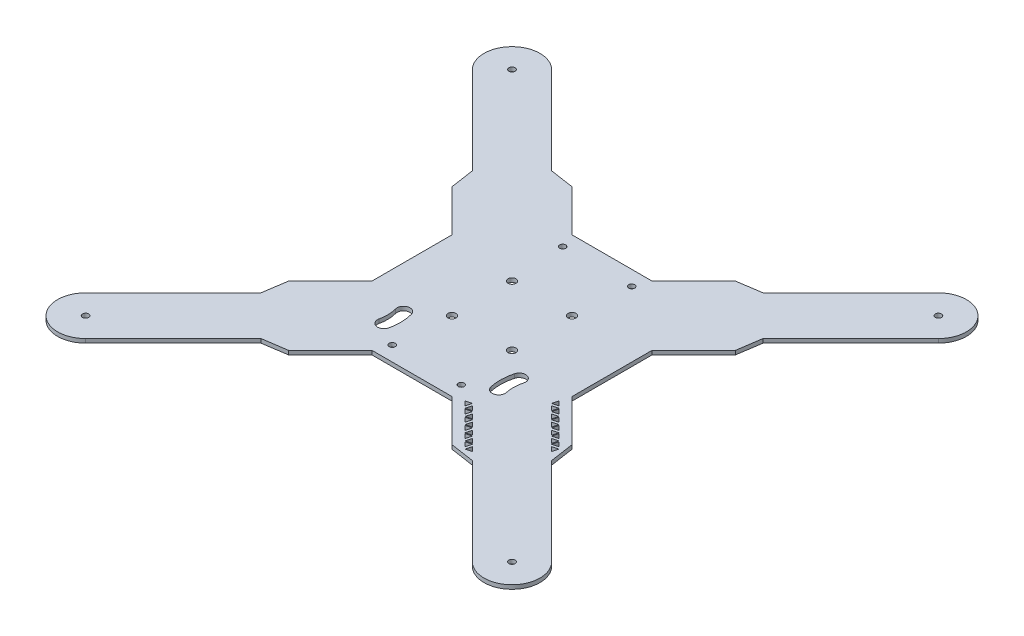
SolidWorks part; units mm, degrees
ref_plane "Front Plane" through (0, 0, 0) normal (0, 0, 1) x (1, 0, 0)
ref_plane "Top Plane" through (0, 0, 0) normal (0, 1, 0) x (1, 0, 0)
ref_plane "Right Plane" through (0, 0, 0) normal (1, 0, 0) x (0, 0, -1)
sketch "Sketch1" plane through (0, 0, 0) normal (0, 1, 0) x (1, 0, 0)
  line L0 (50, 50) -> (106.5685, 106.5685) construction
  line L1 (-50, 50) -> (50, 50)
  line L2 (-50, 50) -> (-50, -50)
  line L3 (-50, -50) -> (50, -50)
  line L4 (50, 50) -> (50, -50)
  line L5 (-50, 50) -> (50, -50) construction
  line L6 (-50, -50) -> (50, 50) construction
  line L7 (0, 97.9754) -> (0, -94.9622) construction
  line L8 (72.6274, 52.8284) -> (70.8284, 40.8284)
  line L9 (70.8284, 40.8284) -> (50, 20)
  line L10 (-86.7005, 0) -> (97.3001, 0) construction
  line L11 (-116.468, 96.669) -> (-72.6274, 52.8284)
  line L12 (-50, 50) -> (-106.5685, 106.5685) construction
  line L13 (-40.8284, 70.8284) -> (-20, 50)
  line L14 (40.8284, 70.8284) -> (20, 50)
  line L15 (-50, -50) -> (-106.5685, -106.5685) construction
  line L16 (50, -50) -> (106.5685, -106.5685) construction
  line L17 (52.8284, 72.6274) -> (40.8284, 70.8284)
  line L18 (96.669, 116.468) -> (52.8284, 72.6274)
  line L19 (116.468, 96.669) -> (72.6274, 52.8284)
  line L20 (-50, -50) -> (50, -50)
  line L21 (50, -50) -> (106.5685, -106.5685) construction
  line L22 (116.468, -96.669) -> (72.6274, -52.8284)
  line L23 (96.669, -116.468) -> (52.8284, -72.6274)
  line L24 (52.8284, -72.6274) -> (40.8284, -70.8284)
  line L25 (-72.6274, 52.8284) -> (-70.8284, 40.8284)
  line L26 (-70.8284, 40.8284) -> (-50, 20)
  line L27 (-52.8284, 72.6274) -> (-40.8284, 70.8284)
  line L28 (-96.669, 116.468) -> (-52.8284, 72.6274)
  line L29 (40.8284, -70.8284) -> (20, -50)
  line L30 (70.8284, -40.8284) -> (50, -20)
  line L31 (72.6274, -52.8284) -> (70.8284, -40.8284)
  line L32 (-50, -50) -> (-106.5685, -106.5685) construction
  line L33 (-96.669, -116.468) -> (-52.8284, -72.6274)
  line L34 (-52.8284, -72.6274) -> (-40.8284, -70.8284)
  line L35 (-70.8284, -40.8284) -> (-50, -20)
  line L36 (-72.6274, -52.8284) -> (-70.8284, -40.8284)
  line L37 (-40.8284, -70.8284) -> (-20, -50)
  line L38 (-116.468, -96.669) -> (-72.6274, -52.8284)
  circle A0 centre (106.5685, 106.5685) radius 14
  circle A1 centre (-106.5685, 106.5685) radius 14
  circle A2 centre (-106.5685, -106.5685) radius 14
  circle A3 centre (106.5685, -106.5685) radius 14
  circle A4 centre (-106.5685, -106.5685) radius 1.556
  circle A5 centre (106.5685, -106.5685) radius 1.556
  circle A6 centre (106.5685, 106.5685) radius 1.556
  circle A7 centre (-106.5685, 106.5685) radius 1.556
  circle A8 centre (106.5685, -106.5685) radius 1.556
  circle A9 centre (-106.5685, -106.5685) radius 1.556
  point P0 (0, 0)
  dimension "D3" = 28
  dimension "D4" = 3.112
  dimension "D1" = 100
  dimension "D2" = 100
  dimension "D5" = 80
  dimension "D6" = 12
  dimension "D7" = 30
  dimension "D8" = 62
  dimension "D9" = 29.4558
extrude "Boss-Extrude1" add sketch "Sketch1" along normal blind 2
sketch "Sketch2" plane through (0, 0, 0) normal (1, 0, 0) x (0, 0, -1)
  line L0 (0, 0) -> (0, 60) construction
  dimension "D1" = 60
sketch "Sketch3" plane through (0, 2, 0) normal (0, 1, 0) x (1, 0, 0)
  line L0 (0, 50) -> (0, -50) construction
  line L1 (-20, 50) -> (20, 50) construction
  line L2 (-20, -50) -> (20, -50) construction
  line L3 (-17.25, 50) -> (-17.25, -50) construction
  line L4 (17.25, 50) -> (17.25, -50) construction
  line L5 (-17.25, 0) -> (17.25, 0) construction
  circle A8 centre (-15, 15) radius 2
  circle A9 centre (-17.25, 42.6) radius 1.5
  circle A10 centre (15, 15) radius 2
  circle A11 centre (17.25, 42.6) radius 1.5
  circle A12 centre (15, -15) radius 2
  circle A13 centre (-15, -15) radius 2
  circle A14 centre (17.25, -42.6) radius 1.5
  circle A15 centre (-17.25, -42.6) radius 1.5
  dimension "D2" = 4
  dimension "D3" = 15
  dimension "D4" = 27.6
  dimension "D5" = 3
  dimension "D6" = 15
  dimension "D7" = 17.25
  dimension "D1" = 17.25
extrude "Cut-Extrude1" cut sketch "Sketch3" against normal blind 10
sketch "Sketch4" plane through (0, 2, 0) normal (0, 1, 0) x (1, 0, 0)
  line L0 (0, -24.6733) -> (0, 24.6733) construction
  arc A0 (28.8923, -25.3253) -> (28.6598, -35.3226) centre (49.6054, -30.8083) ccw construction
  arc A5 (25.7505, -24.4936) -> (25.4828, -36.0073) centre (49.6054, -30.8083) ccw
  arc A6 (32.0341, -26.1569) -> (31.8369, -34.6378) centre (49.6054, -30.8083) ccw
  arc A7 (32.0341, -26.1569) -> (25.7505, -24.4936) centre (28.8923, -25.3253) ccw
  arc A8 (25.4828, -36.0073) -> (31.8369, -34.6378) centre (28.6598, -35.3226) ccw
  arc A9 (-28.8923, -25.3253) -> (-28.6598, -35.3226) centre (-49.6054, -30.8083) cw construction
  arc A10 (-25.7505, -24.4936) -> (-25.4828, -36.0073) centre (-49.6054, -30.8083) cw
  arc A11 (-32.0341, -26.1569) -> (-31.8369, -34.6378) centre (-49.6054, -30.8083) cw
  arc A12 (-32.0341, -26.1569) -> (-25.7505, -24.4936) centre (-28.8923, -25.3253) cw
  arc A13 (-25.4828, -36.0073) -> (-31.8369, -34.6378) centre (-28.6598, -35.3226) cw
  point P3 (28.1847, -30.3102)
  point P8 (48.4255, -30.805)
  point P9 (28.5792, -22.729)
  point P10 (25.9159, -28.1417)
  point P11 (49.9586, -24.5797)
  point P17 (-28.1847, -30.3102)
  dimension "D1" = 10
  dimension "D2" = 6.5
extrude "Cut-Extrude2" cut sketch "Sketch4" against normal through all both
sketch "Sketch5" plane through (0, 2, 0) normal (0, 1, 0) x (1, 0, 0)
  line L0 (25.1819, -48.6551) -> (27.3032, -50.7765)
  line L3 (25.1819, -48.6551) -> (28.0797, -47.8787)
  line L4 (28.0797, -47.8787) -> (27.3032, -50.7765)
  line L12 (116.468, -116.468) -> (36.1807, -36.1807) construction
  line L25 (40.8284, -70.8284) -> (20, -50) construction
  line L26 (52.8284, -72.6274) -> (28.0797, -47.8787) construction
  line L30 (27.3032, -50.7765) -> (48.5062, -71.9795) construction
  line L31 (52.8284, -72.6274) -> (40.8284, -70.8284) construction
  line L32 (29.0797, -48.8787) -> (28.3032, -51.7765)
  line L33 (28.3032, -51.7765) -> (31.201, -51)
  line L34 (31.201, -51) -> (29.0797, -48.8787)
  line L35 (28.7174, -52.1907) -> (30.8388, -54.312)
  line L36 (28.7174, -52.1907) -> (31.6152, -51.4142)
  line L37 (31.6152, -51.4142) -> (30.8388, -54.312)
  line L38 (32.6152, -52.4142) -> (31.8388, -55.312)
  line L39 (31.8388, -55.312) -> (34.7365, -54.5355)
  line L40 (34.7365, -54.5355) -> (32.6152, -52.4142)
  line L41 (32.253, -55.7262) -> (34.3743, -57.8475)
  line L42 (32.253, -55.7262) -> (35.1508, -54.9497)
  line L43 (35.1508, -54.9497) -> (34.3743, -57.8475)
  line L44 (36.1508, -55.9497) -> (35.3743, -58.8475)
  line L45 (35.3743, -58.8475) -> (38.2721, -58.0711)
  line L46 (38.2721, -58.0711) -> (36.1508, -55.9497)
  line L47 (35.7885, -59.2617) -> (37.9098, -61.3831)
  line L48 (35.7885, -59.2617) -> (38.6863, -58.4853)
  line L49 (38.6863, -58.4853) -> (37.9098, -61.3831)
  line L50 (39.6863, -59.4853) -> (38.9098, -62.3831)
  line L51 (38.9098, -62.3831) -> (41.8076, -61.6066)
  line L52 (41.8076, -61.6066) -> (39.6863, -59.4853)
  line L53 (39.324, -62.7973) -> (41.4454, -64.9186)
  line L54 (39.324, -62.7973) -> (42.2218, -62.0208)
  line L55 (42.2218, -62.0208) -> (41.4454, -64.9186)
  line L56 (43.2218, -63.0208) -> (42.4454, -65.9186)
  line L57 (42.4454, -65.9186) -> (45.3431, -65.1421)
  line L58 (45.3431, -65.1421) -> (43.2218, -63.0208)
  line L59 (42.8596, -66.3328) -> (44.9809, -68.4541)
  line L60 (42.8596, -66.3328) -> (45.7574, -65.5563)
  line L61 (45.7574, -65.5563) -> (44.9809, -68.4541)
  line L62 (46.7574, -66.5563) -> (45.9809, -69.4541)
  line L63 (45.9809, -69.4541) -> (48.8787, -68.6777)
  line L64 (48.8787, -68.6777) -> (46.7574, -66.5563)
  line L65 (96.669, -116.468) -> (52.8284, -72.6274) construction
  line L66 (68.6777, -48.8787) -> (66.5563, -46.7574)
  line L67 (69.4541, -45.9809) -> (68.6777, -48.8787)
  line L68 (66.5563, -46.7574) -> (69.4541, -45.9809)
  line L69 (65.5563, -45.7574) -> (68.4541, -44.9809)
  line L70 (66.3328, -42.8596) -> (65.5563, -45.7574)
  line L71 (66.3328, -42.8596) -> (68.4541, -44.9809)
  line L72 (65.1421, -45.3431) -> (63.0208, -43.2218)
  line L73 (65.9186, -42.4454) -> (65.1421, -45.3431)
  line L74 (63.0208, -43.2218) -> (65.9186, -42.4454)
  line L75 (62.0208, -42.2218) -> (64.9186, -41.4454)
  line L76 (62.7973, -39.324) -> (62.0208, -42.2218)
  line L77 (62.7973, -39.324) -> (64.9186, -41.4454)
  line L78 (61.6066, -41.8076) -> (59.4853, -39.6863)
  line L79 (62.3831, -38.9098) -> (61.6066, -41.8076)
  line L80 (59.4853, -39.6863) -> (62.3831, -38.9098)
  line L81 (58.4853, -38.6863) -> (61.3831, -37.9098)
  line L82 (59.2617, -35.7885) -> (58.4853, -38.6863)
  line L83 (59.2617, -35.7885) -> (61.3831, -37.9098)
  line L84 (58.0711, -38.2721) -> (55.9497, -36.1508)
  line L85 (58.8475, -35.3743) -> (58.0711, -38.2721)
  line L86 (55.9497, -36.1508) -> (58.8475, -35.3743)
  line L87 (54.9497, -35.1508) -> (57.8475, -34.3743)
  line L88 (55.7262, -32.253) -> (54.9497, -35.1508)
  line L89 (55.7262, -32.253) -> (57.8475, -34.3743)
  line L90 (54.5355, -34.7365) -> (52.4142, -32.6152)
  line L91 (55.312, -31.8388) -> (54.5355, -34.7365)
  line L92 (52.4142, -32.6152) -> (55.312, -31.8388)
  line L93 (51.4142, -31.6152) -> (54.312, -30.8388)
  line L94 (52.1907, -28.7174) -> (51.4142, -31.6152)
  line L95 (52.1907, -28.7174) -> (54.312, -30.8388)
  line L96 (51, -31.201) -> (48.8787, -29.0797)
  line L97 (51.7765, -28.3032) -> (51, -31.201)
  line L98 (48.8787, -29.0797) -> (51.7765, -28.3032)
  line L99 (47.8787, -28.0797) -> (50.7765, -27.3032)
  line L100 (48.6551, -25.1819) -> (47.8787, -28.0797)
  line L101 (48.6551, -25.1819) -> (50.7765, -27.3032)
  arc A0 (96.669, -116.468) -> (116.468, -96.669) centre (106.5685, -106.5685) ccw construction
  dimension "D2" = 1
  dimension "D3" = 3
  dimension "D4" = 5.5858
  dimension "D5" = 6
  dimension "D1" = 35
extrude "Cut-Extrude3" cut sketch "Sketch5" against normal through all both
